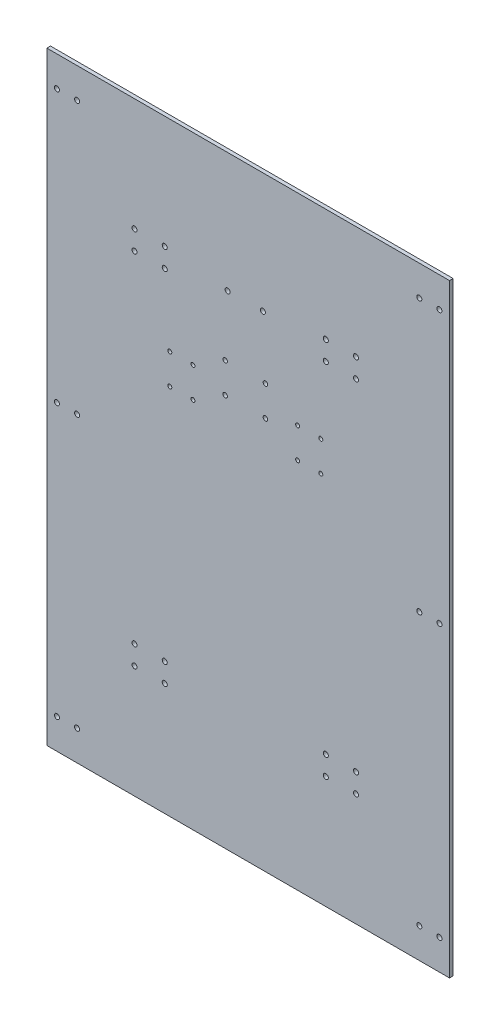
SolidWorks part; units mm, degrees
material "处理板，复杂型"
ref_plane "前视基准面" through (0, 0, 0) normal (0, 0, 1) x (1, 0, 0)
ref_plane "上视基准面" through (0, 0, 0) normal (0, 1, 0) x (1, 0, 0)
ref_plane "右视基准面" through (0, 0, 0) normal (1, 0, 0) x (0, 0, -1)
sketch "草图1" plane through (0, 0, 0) normal (0, 0, 1) x (1, 0, 0)
  line L0 (0, 25.8706) -> (0, -31.2111) construction
  line L1 (-225, 300) -> (175, 300)
  line L2 (-225, 300) -> (-225, -300)
  line L3 (-225, -300) -> (175, -300)
  line L4 (175, 300) -> (175, -300)
  line L5 (-23.9883, 0) -> (45.7004, 0) construction
  dimension "D1" = 400
  dimension "D2" = 600
  dimension "D3" = 225
  dimension "D4" = 300
extrude "凸台-拉伸1" add sketch "草图1" along normal blind 3.6
sketch "草图4" plane through (0, 0, 3.6) normal (0, 0, 1) x (1, 0, 0)
  line L0 (0, 355.7202) -> (0, -488.737) construction
  line L1 (-385.3696, 0) -> (469.6692, 0) construction
  line L2 (-195, 355.7202) -> (-195, -398.416) construction
  line L3 (145, -398.416) -> (145, 398.416) construction
  line L4 (-371.3197, 270) -> (369.3125, 270) construction
  line L5 (-343.2198, -270) -> (413.4695, -270) construction
  line L6 (175, -300) -> (175, 300) construction
  line L8 (-225, 300) -> (-225, -300) construction
  line L9 (-225, -300) -> (175, -300) construction
  line L10 (-205, -325.8576) -> (-205, 461.6631) construction
  line L11 (205, -325.8576) -> (205, 461.6631) construction
  circle A0 centre (-195, 270) radius 2.5
  circle A1 centre (-195, -270) radius 2.5
  circle A4 centre (-195, 0) radius 2.5
  circle A7 centre (-215, -270) radius 2.5
  circle A8 centre (-215, 0) radius 2.5
  circle A9 centre (-215, 270) radius 2.5
  dimension "D5" = 5
  dimension "D7" = 5
  dimension "D10" = 5
  dimension "D1" = 30
  dimension "D3" = 30
  dimension "D4" = 30
  dimension "D11" = 10
extrude "切除-拉伸3" cut sketch "草图4" against normal blind 3.6
sketch "草图5" plane through (0, 0, 3.6) normal (0, 0, 1) x (1, 0, 0)
  circle A0 centre (-102.8839, 69.956) radius 2
  circle A1 centre (-102.8839, 99.956) radius 2
  circle A2 centre (-79.8839, 69.956) radius 2
  circle A3 centre (-79.8839, 99.956) radius 2
extrude "切除-拉伸4" cut sketch "草图5" against normal blind 10
sketch "草图6" plane through (0, 0, 3.6) normal (0, 0, 1) x (1, 0, 0)
  circle A0 centre (24.1161, 69.956) radius 2
  circle A1 centre (24.1161, 99.956) radius 2
  circle A2 centre (47.1161, 69.956) radius 2
  circle A3 centre (47.1161, 99.956) radius 2
extrude "切除-拉伸5" cut sketch "草图6" against normal blind 10
sketch "草图7" plane through (0, 0, 3.6) normal (0, 0, 1) x (1, 0, 0)
  circle A0 centre (-45.3839, 180.956) radius 2.5
  circle A1 centre (-10.3839, 180.956) radius 2.5
extrude "切除-拉伸6" cut sketch "草图7" against normal blind 10
sketch "草图8" plane through (0, 0, 3.6) normal (0, 0, 1) x (1, 0, 0)
  circle A0 centre (-47.8839, 89.956) radius 2.25
  circle A1 centre (-47.8839, 119.956) radius 2.25
  circle A2 centre (-7.8839, 89.956) radius 2.25
  circle A3 centre (-7.8839, 119.956) radius 2.25
extrude "切除-拉伸7" cut sketch "草图8" against normal through all
sketch "草图9" plane through (0, 0, 3.6) normal (0, 0, 1) x (1, 0, 0)
  circle A0 centre (-137.8839, -188.044) radius 2.5
  circle A1 centre (-137.8839, -169.044) radius 2.5
  circle A2 centre (-107.8839, -188.044) radius 2.5
  circle A3 centre (-107.8839, -169.044) radius 2.5
  circle A4 centre (52.1161, -188.044) radius 2.5
  circle A5 centre (52.1161, -169.044) radius 2.5
  circle A6 centre (82.1161, -169.044) radius 2.5
  circle A7 centre (82.1161, -188.044) radius 2.5
  circle A8 centre (82.1161, 168.956) radius 2.5
  circle A9 centre (82.1161, 187.956) radius 2.5
  circle A10 centre (52.1161, 168.956) radius 2.5
  circle A11 centre (52.1161, 187.956) radius 2.5
  circle A12 centre (-107.8839, 168.956) radius 2.5
  circle A13 centre (-107.8839, 187.956) radius 2.5
  circle A14 centre (-137.8839, 168.956) radius 2.5
  circle A15 centre (-137.8839, 187.956) radius 2.5
extrude "切除-拉伸8" cut sketch "草图9" against normal through all
ref_plane "基准面1" through (-25, 0, 0) normal (-1, 0, 0) x (0, 0, 1)
mirror "镜向1" about plane through (-25, 0, 0) normal (-1, 0, 0) of "切除-拉伸3"
